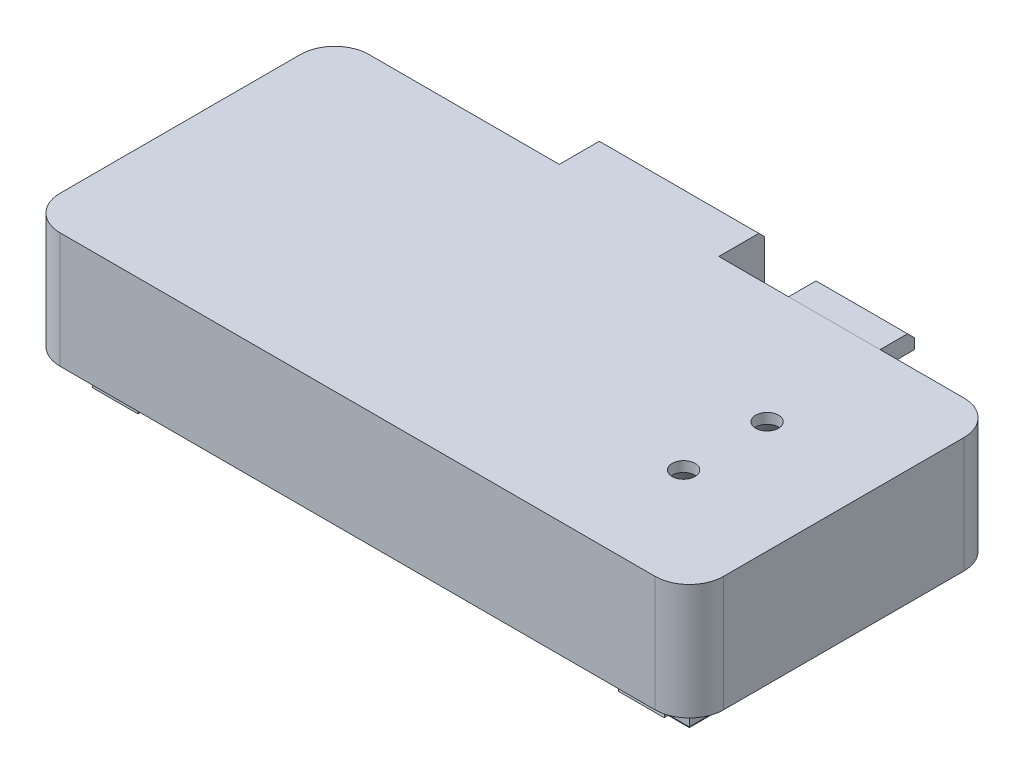
SolidWorks part; units mm, degrees
ref_plane "Front Plane" through (0, 0, 0) normal (0, 0, 1) x (1, 0, 0)
ref_plane "Top Plane" through (0, 0, 0) normal (0, 1, 0) x (1, 0, 0)
ref_plane "Right Plane" through (0, 0, 0) normal (1, 0, 0) x (0, 0, -1)
sketch "Sketch2" plane through (0, -591.8028, 0) normal (0, 1, 0) x (1, 0, 0)
  line L1 (-23.1805, -11.0534) -> (-23.1805, -19.9534)
  line L2 (-21.1805, -19.9534) -> (-21.1805, -11.0534)
  line L13 (34.8195, -25.4534) -> (34.8195, -4.4534)
  line L14 (31.8195, -1.4534) -> (-20.1805, -1.4534)
  line L15 (-23.1805, -4.4534) -> (-23.1805, -11.0534)
  line L16 (-23.1805, -11.0534) -> (-21.1805, -11.0534)
  line L17 (-21.1805, -11.0534) -> (-21.1805, -3.4534)
  line L18 (-21.1805, -3.4534) -> (-19.6805, -3.4534)
  line L19 (32.8195, -3.4534) -> (32.8195, -26.4534)
  line L20 (32.8195, -26.4534) -> (31.3195, -26.4534)
  line L21 (-21.1805, -26.4534) -> (-21.1805, -19.9534)
  line L22 (-21.1805, -19.9534) -> (-23.1805, -19.9534)
  line L23 (-23.1805, -19.9534) -> (-23.1805, -25.4534)
  line L24 (-20.1805, -28.4534) -> (31.8195, -28.4534)
  line L25 (34.8195, -25.4534) -> (34.8195, -4.4534)
  line L26 (31.8195, -1.4534) -> (-20.1805, -1.4534)
  line L27 (-23.1805, -4.4534) -> (-23.1805, -11.0534)
  line L28 (-23.1805, -11.0534) -> (-21.1805, -11.0534)
  line L29 (-21.1805, -11.0534) -> (-21.1805, -3.4534)
  line L30 (-21.1805, -3.4534) -> (-19.6805, -3.4534)
  line L31 (32.8195, -3.4534) -> (32.8195, -26.4534)
  line L32 (32.8195, -26.4534) -> (31.3195, -26.4534)
  line L33 (-21.1805, -26.4534) -> (-21.1805, -19.9534)
  line L34 (-21.1805, -19.9534) -> (-23.1805, -19.9534)
  line L35 (-23.1805, -19.9534) -> (-23.1805, -25.4534)
  line L36 (-20.1805, -28.4534) -> (31.8195, -28.4534)
  line L131 (26.3195, -3.4534) -> (31.3195, -3.4534)
  line L132 (26.3195, -3.4534) -> (31.3195, -3.4534)
  line L133 (31.3195, -3.4534) -> (32.8195, -3.4534)
  line L134 (31.3195, -3.4534) -> (32.8195, -3.4534)
  line L135 (31.3195, -26.4534) -> (26.3195, -26.4534)
  line L136 (31.3195, -26.4534) -> (26.3195, -26.4534)
  line L137 (-19.6805, -26.4534) -> (-21.1805, -26.4534)
  line L138 (-19.6805, -26.4534) -> (-21.1805, -26.4534)
  line L163 (-19.6805, -3.4534) -> (-14.6805, -3.4534)
  line L164 (-19.6805, -3.4534) -> (-14.6805, -3.4534)
  line L165 (-14.6805, -3.4534) -> (26.3195, -3.4534)
  line L166 (-14.6805, -3.4534) -> (26.3195, -3.4534)
  line L167 (26.3195, -26.4534) -> (-14.6805, -26.4534)
  line L168 (26.3195, -26.4534) -> (-14.6805, -26.4534)
  line L169 (-14.6805, -26.4534) -> (-19.6805, -26.4534)
  line L170 (-14.6805, -26.4534) -> (-19.6805, -26.4534)
  arc A4 (34.8195, -4.4534) -> (31.8195, -1.4534) centre (31.8195, -4.4534) ccw
  arc A5 (-20.1805, -1.4534) -> (-23.1805, -4.4534) centre (-20.1805, -4.4534) ccw
  arc A6 (-23.1805, -25.4534) -> (-20.1805, -28.4534) centre (-20.1805, -25.4534) ccw
  arc A7 (31.8195, -28.4534) -> (34.8195, -25.4534) centre (31.8195, -25.4534) ccw
  arc A8 (34.8195, -4.4534) -> (31.8195, -1.4534) centre (31.8195, -4.4534) ccw
  arc A9 (-20.1805, -1.4534) -> (-23.1805, -4.4534) centre (-20.1805, -4.4534) ccw
  arc A10 (-23.1805, -25.4534) -> (-20.1805, -28.4534) centre (-20.1805, -25.4534) ccw
  arc A11 (31.8195, -28.4534) -> (34.8195, -25.4534) centre (31.8195, -25.4534) ccw
  line M17 (34.8195, -25.4534) -> (34.8195, -4.4534)
  arc M18 (34.8195, -4.4534) -> (31.8195, -1.4534) centre (31.8195, -4.4534) ccw
  line M19 (31.8195, -1.4534) -> (-20.1805, -1.4534)
  arc M20 (-20.1805, -1.4534) -> (-23.1805, -4.4534) centre (-20.1805, -4.4534) ccw
  line M21 (-23.1805, -4.4534) -> (-23.1805, -11.0534)
  line M22 (-23.1805, -11.0534) -> (-21.1805, -11.0534)
  line M23 (-21.1805, -11.0534) -> (-21.1805, -3.4534)
  line M24 (-21.1805, -3.4534) -> (-19.6805, -3.4534)
  line M25 (32.8195, -3.4534) -> (32.8195, -26.4534)
  line M26 (32.8195, -26.4534) -> (31.3195, -26.4534)
  line M27 (-21.1805, -26.4534) -> (-21.1805, -19.9534)
  line M28 (-21.1805, -19.9534) -> (-23.1805, -19.9534)
  line M29 (-23.1805, -19.9534) -> (-23.1805, -25.4534)
  arc M30 (-23.1805, -25.4534) -> (-20.1805, -28.4534) centre (-20.1805, -25.4534) ccw
  line M31 (-20.1805, -28.4534) -> (31.8195, -28.4534)
  arc M32 (31.8195, -28.4534) -> (34.8195, -25.4534) centre (31.8195, -25.4534) ccw
  dimension "D1" = 0
extrude "Boss-Extrude1" add sketch "Sketch2" along normal blind 8.108 contours M32 M17 M18 M19 M20 M21 M22 M23 M24 M25 M26 M27 M28 M29 M30 M31 | L2 L1 M28 M22
sketch "Sketch3" plane through (0, -583.6948, 0) normal (0, 1, 0) x (1, 0, 0)
  line L4 (34.8195, -25.4534) -> (34.8195, -4.4534)
  line L5 (31.8195, -1.4534) -> (-20.1805, -1.4534)
  line L6 (-23.1805, -4.4534) -> (-23.1805, -25.4534)
  line L7 (-20.1805, -28.4534) -> (31.8195, -28.4534)
  line L8 (34.8195, -25.4534) -> (34.8195, -4.4534)
  line L9 (31.8195, -1.4534) -> (-20.1805, -1.4534)
  line L10 (-23.1805, -4.4534) -> (-23.1805, -25.4534)
  line L11 (-20.1805, -28.4534) -> (31.8195, -28.4534)
  arc A4 (31.8195, -28.4534) -> (34.8195, -25.4534) centre (31.8195, -25.4534) ccw
  arc A5 (34.8195, -4.4534) -> (31.8195, -1.4534) centre (31.8195, -4.4534) ccw
  arc A6 (-20.1805, -1.4534) -> (-23.1805, -4.4534) centre (-20.1805, -4.4534) ccw
  arc A7 (-23.1805, -25.4534) -> (-20.1805, -28.4534) centre (-20.1805, -25.4534) ccw
  arc A8 (31.8195, -28.4534) -> (34.8195, -25.4534) centre (31.8195, -25.4534) ccw
  arc A9 (34.8195, -4.4534) -> (31.8195, -1.4534) centre (31.8195, -4.4534) ccw
  arc A10 (-20.1805, -1.4534) -> (-23.1805, -4.4534) centre (-20.1805, -4.4534) ccw
  arc A11 (-23.1805, -25.4534) -> (-20.1805, -28.4534) centre (-20.1805, -25.4534) ccw
  dimension "D1" = 0
extrude "Boss-Extrude2" add sketch "Sketch3" along normal blind 2
sketch "Sketch4" plane through (0, -583.6948, 0) normal (0, -1, 0) x (1, 0, 0)
  line L0 (26.8195, 26.4534) -> (32.8195, 26.4534)
  line L1 (32.8195, 26.4534) -> (-21.1805, 26.4534) construction
  line L2 (32.8195, 26.4534) -> (32.8195, 24.4534)
  line L3 (32.8195, 3.4534) -> (32.8195, 26.4534) construction
  line L4 (32.8195, 24.4534) -> (26.8195, 24.4534)
  line L5 (26.8195, 24.4534) -> (26.8195, 26.4534)
  line L6 (32.8195, 5.4534) -> (26.8195, 5.4534)
  line L7 (26.8195, 5.4534) -> (26.8195, 3.4534)
  line L8 (-21.1805, 3.4534) -> (32.8195, 3.4534) construction
  line L9 (26.8195, 3.4534) -> (32.8195, 3.4534)
  line L10 (32.8195, 3.4534) -> (32.8195, 5.4534)
  line L11 (-21.1805, 26.4534) -> (-15.1805, 26.4534)
  line L12 (-15.1805, 26.4534) -> (-15.1805, 24.4534)
  line L13 (-15.1805, 24.4534) -> (-21.1805, 24.4534)
  line L14 (-21.1805, 26.4534) -> (-21.1805, 3.4534) construction
  line L15 (-21.1805, 24.4534) -> (-21.1805, 26.4534)
  line L16 (-21.1805, 5.4534) -> (-15.1805, 5.4534)
  line L17 (-15.1805, 5.4534) -> (-15.1805, 3.4534)
  line L18 (-15.1805, 3.4534) -> (-21.1805, 3.4534)
  line L19 (-21.1805, 3.4534) -> (-21.1805, 5.4534)
  line L21 (-0.6397, 26.4534) -> (6.2386, 26.4534)
  line L22 (-0.6397, 26.4534) -> (-0.6397, 24.4534)
  line L23 (-0.6397, 24.4534) -> (6.2386, 24.4534)
  line L24 (6.2386, 26.4534) -> (6.2386, 24.4534)
  dimension "D1" = 6
  dimension "D2" = 2
extrude "Boss-Extrude3" add sketch "Sketch4" along normal offset from surface (10.108 mm away) 2 up to face at (5.8195, -591.8028, 14.9534) offset beyond the face yes
sketch "Sketch5" plane through (0, -581.6948, 0) normal (0, 1, 0) x (1, 0, 0)
  line L0 (32.8195, -5.4534) -> (32.8195, -24.4534) construction
  line L1 (26.8195, -26.4534) -> (6.2386, -26.4534) construction
  circle A0 centre (25.0195, -11.8534) radius 1
  circle A1 centre (25.0195, -19.1534) radius 1
  dimension "D1" = 7.3
  dimension "D2" = 2
  dimension "D3" = 7.8
  dimension "D4" = 7.3
extrude "Cut-Extrude1" cut sketch "Sketch5" against normal up to next
chamfer "Chamfer1" distance 0.8 angle 54 2 edges at (25.0195, -583.6948, 12.8534) (25.0195, -583.6948, 20.1534)
sketch "Sketch6" plane through (26.8195, 0, 0) normal (-1, 0, 0) x (0, 0, 1)
  line L0 (3.4534, -592.8028) -> (3.2534, -593.8028)
  line L1 (3.4534, -593.8028) -> (3.4534, -591.8028) construction
  line L2 (3.2534, -593.8028) -> (3.4534, -593.8028)
  line L3 (3.4534, -593.8028) -> (3.4534, -592.8028)
  line L4 (3.4534, -593.8028) -> (5.4534, -593.8028) construction
  line L5 (26.4534, -593.8028) -> (26.6534, -593.8028)
  line L6 (26.6534, -593.8028) -> (26.4534, -592.8028)
  line L7 (26.4534, -591.8028) -> (26.4534, -583.6948) construction
  line L8 (26.4534, -592.8028) -> (26.4534, -593.8028)
  point P11 (0, 0)
  dimension "D1" = 0.2
  dimension "D2" = 1
extrude "Boss-Extrude4" add sketch "Sketch6" against normal offset from surface (4 mm away) 2 up to face at (32.8195, -592.8028, 4.4534)
sketch "Sketch7" plane through (-15.1805, 0, 0) normal (1, 0, 0) x (0, 0, -1)
  line L5 (-26.4534, -593.8028) -> (-26.6534, -593.8028)
  line L6 (-26.6534, -593.8028) -> (-26.4534, -591.8028)
  line L7 (-26.4534, -591.8028) -> (-26.4534, -593.8028)
  line L8 (-3.4534, -593.8028) -> (-3.2534, -593.8028)
  line L9 (-3.2534, -593.8028) -> (-3.4534, -591.8028)
  line L10 (-3.4534, -593.8028) -> (-3.4534, -591.8028) construction
  line L11 (-3.4534, -591.8028) -> (-3.4534, -593.8028)
  line L12 (-5.4534, -593.8028) -> (-3.4534, -593.8028) construction
  point P2 (-2.3575, -2.8108)
  point P7 (-2.9015, -0.8108)
  point P10 (-2.7015, -2.8108)
  dimension "D3" = 2
  dimension "D4" = 0.2
extrude "Boss-Extrude5" add sketch "Sketch7" against normal offset from surface (4 mm away) 2 up to face at (-21.1805, -592.8028, 25.4534)
chamfer "Chamfer2" distance 0.15 angle 54 15 edges at (28.8195, -593.8028, 3.2534) (-17.1805, -593.8028, 3.2534) (-21.1805, -593.8028, 25.4534) (-20.1805, -593.8028, 26.4534) (2.7994, -593.8028, 26.4534) (31.8195, -593.8028, 26.4534) (32.8195, -593.8028, 25.4534) (26.8195, -593.8028, 4.3534) (29.8195, -593.8028, 5.4534) (32.8195, -593.8028, 4.4534) (31.8195, -593.8028, 3.4534) (-15.1805, -593.8028, 4.3534) (-20.1805, -593.8028, 3.4534) (-21.1805, -593.8028, 4.4534) (-18.1805, -593.8028, 5.4534)
sketch "Sketch9" plane through (0, 0, 3.4534) normal (0, 0, 1) x (1, 0, 0)
  line L0 (17.9568, -584.9948) -> (23.0368, -584.9948) construction
  line L1 (-15.1805, -583.6948) -> (26.8195, -583.6948) construction
  circle A0 centre (17.9568, -584.9948) radius 0.75
  circle A1 centre (20.4968, -584.9948) radius 0.75
  circle A2 centre (23.0368, -584.9948) radius 0.75
  dimension "D1" = 5.08
  dimension "D2" = 1.5
  dimension "D3" = 1.3
extrude "Cut-Extrude3" cut sketch "Sketch9" against normal up to next
sketch "Sketch10" plane through (0, 0, 1.4534) normal (0, 0, -1) x (-1, 0, 0)
  line L0 (-16.9968, -584.9948) -> (-23.9968, -584.9948) construction
  line L1 (-16.9968, -586.7448) -> (-23.9968, -586.7448)
  line L2 (-16.9968, -583.2448) -> (-23.9968, -583.2448)
  arc A0 (-16.9968, -586.7448) -> (-16.9968, -583.2448) centre (-16.9968, -584.9948) ccw
  arc A1 (-23.9968, -583.2448) -> (-23.9968, -586.7448) centre (-23.9968, -584.9948) ccw
  circle A2 centre (-20.4968, -584.9948) radius 0.75 construction
  point P2 (-20.4968, -584.9948)
  point P7 (0, 0)
  dimension "D1" = 3.5
  dimension "D2" = 7
extrude "Cut-Extrude4" cut sketch "Sketch10" against normal blind 1.2 draft 45
sketch "Sketch11" plane through (0, -583.6948, 0) normal (0, -1, 0) x (1, 0, 0)
  line L0 (20.4968, 3.4534) -> (20.4968, 6.9934) construction
  line L1 (-15.1805, 3.4534) -> (26.8195, 3.4534) construction
  line L2 (21.2468, 3.4534) -> (19.7468, 3.4534) construction
  line L3 (23.8031, 6.9934) -> (23.8031, 8.9934)
  line L4 (16.4968, 6.9934) -> (24.4968, 6.9934)
  line L5 (16.4968, 6.9934) -> (16.4968, 8.9934)
  line L6 (16.4968, 8.9934) -> (24.4968, 8.9934)
  line L7 (24.4968, 6.9934) -> (24.4968, 8.9934)
  line L8 (24.4968, 3.4534) -> (16.4968, 3.4534)
  line L9 (24.4968, 3.4534) -> (24.4968, 4.4534)
  line L10 (24.4968, 4.4534) -> (16.4968, 4.4534)
  line L11 (16.4968, 3.4534) -> (16.4968, 4.4534)
  line L12 (23.8031, 3.4534) -> (22.6031, 3.4534)
  line L13 (23.8031, 3.4534) -> (23.8031, 4.4534)
  line L14 (23.8031, 4.4534) -> (22.6031, 4.4534)
  line L15 (22.6031, 3.4534) -> (22.6031, 4.4534)
  line L16 (21.0968, 3.4534) -> (19.8968, 3.4534)
  line L17 (21.0968, 3.4534) -> (21.0968, 4.4534)
  line L18 (21.0968, 4.4534) -> (19.8968, 4.4534)
  line L19 (19.8968, 3.4534) -> (19.8968, 4.4534)
  line L20 (18.7335, 3.4534) -> (17.5335, 3.4534)
  line L21 (18.7335, 3.4534) -> (18.7335, 4.4534)
  line L22 (18.7335, 4.4534) -> (17.5335, 4.4534)
  line L23 (17.5335, 3.4534) -> (17.5335, 4.4534)
  line L24 (22.6031, 6.9934) -> (22.6031, 8.9934)
  line L25 (19.8968, 6.9934) -> (19.8968, 8.9934)
  line L26 (21.0968, 6.9934) -> (21.0968, 8.9934)
  line L27 (18.7335, 6.9934) -> (18.7335, 8.9934)
  line L28 (17.5335, 6.9934) -> (17.5335, 8.9934)
  point P26 (20.4968, 3.4534)
  line M9 (-15.1805, 3.4534) -> (26.8195, 3.4534)
  dimension "D1" = 1
  dimension "D2" = 2
  dimension "D3" = 8
  dimension "D4" = 2.54
  dimension "D5" = 0.6
extrude "Boss-Extrude6" add sketch "Sketch11" along normal blind 2.5 contours L13 L9 L10 M9 | L17 L15 L10 M9 | L21 L19 L10 M9 | L23 L10 L11 M9 | L4 L7 L6 L3 | L26 L4 L24 L6 | L27 L4 L25 L6 | L4 L28 L6 L5
sketch "Sketch12" plane through (0, 0, 1.4534) normal (0, 0, -1) x (-1, 0, 0)
  line L0 (-31.8195, -581.6948) -> (20.1805, -581.6948) construction
  line L1 (-24.4968, -581.6948) -> (-16.4968, -581.6948)
  line L2 (-24.4968, -581.6948) -> (-24.4968, -583.1948)
  line L3 (-24.4968, -583.1948) -> (-16.4968, -583.1948)
  line L4 (-16.4968, -581.6948) -> (-16.4968, -583.1948)
  line L5 (-20.4968, -584.9948) -> (-20.4968, -583.1948) construction
  point P6 (-20.4968, -583.1948)
  point P10 (-20.4968, -245.8559)
  point P11 (-20.4968, -245.8559)
  dimension "D1" = 1.5
  dimension "D2" = 8
extrude "Boss-Extrude7" add sketch "Sketch12" along normal blind 3 separate body
chamfer "Chamfer4" distance 0.6 angle 45 3 edges at (16.4968, -581.6948, -0.0466) (24.4968, -581.6948, -0.0466) (20.4968, -581.6948, -1.5466)
sketch "Sketch14" plane through (0, -583.6948, 0) normal (0, -1, 0) x (1, 0, 0)
  line L0 (7.9245, 3.4534) -> (7.9245, 8.9431)
  line L1 (-15.1805, 3.4534) -> (16.4968, 3.4534) construction
  line L2 (7.9245, 8.9431) -> (-1.0755, 8.9431)
  line L3 (-1.0755, 8.9431) -> (-1.0755, 3.4534)
  line L4 (-1.0755, 3.4534) -> (7.9245, 3.4534)
  line L5 (6.6245, 3.4534) -> (6.6245, 8.9431)
  line L6 (5.2245, 3.4534) -> (5.2245, 8.9431)
  line L7 (1.6245, 3.4534) -> (1.6245, 8.9431)
  line L8 (0.2245, 3.4534) -> (0.2245, 8.9431)
  line L9 (3.9245, 3.4534) -> (3.9245, 8.9431)
  line L10 (2.9245, 3.4534) -> (2.9245, 8.9431)
  line L11 (7.9245, 4.4534) -> (-1.0755, 4.4534)
  line L12 (17.5335, 4.4534) -> (16.4968, 4.4534) construction
  line L13 (7.9245, 6.9934) -> (-1.0755, 6.9934)
  line L14 (16.4968, 6.9934) -> (17.5335, 6.9934) construction
  line L15 (3.9245, 6.1982) -> (2.9245, 6.1982) construction
  line L16 (3.4245, 6.1982) -> (3.4245, 4.4534) construction
  point P28 (3.4245, 4.4534)
  line M40 (-15.1805, 3.4534) -> (16.4968, 3.4534)
  dimension "D1" = 1.3
  dimension "D2" = 1.3
  dimension "D3" = 1.3
  dimension "D4" = 1.3
  dimension "D5" = 1
  dimension "D6" = 9
extrude "Boss-Extrude8" add sketch "Sketch14" along normal blind 4 contours L0 L11 L5 L4 | L6 L11 L9 M40 | L10 L11 L7 L4 | L8 L11 L3 M40 | L13 L8 L2 L3 | L13 L10 L2 L7 | L13 L6 L2 L9 | L13 L0 L2 L5
sketch "Sketch15" plane through (0, 0, 3.4534) normal (0, 0, 1) x (1, 0, 0)
  line L0 (5.9645, -584.9948) -> (0.8845, -584.9948) construction
  line L1 (3.9245, -583.6948) -> (2.9245, -583.6948) construction
  line L2 (3.4245, -583.6948) -> (3.4245, -584.9948) construction
  line L3 (7.9245, -583.6948) -> (16.4968, -583.6948) construction
  circle A0 centre (5.9645, -584.9948) radius 0.75
  circle A1 centre (3.4245, -584.9948) radius 0.75
  circle A2 centre (0.8845, -584.9948) radius 0.75
  circle A3 centre (3.4245, -587.5348) radius 0.75
  circle A4 centre (0.8845, -587.5348) radius 0.75
  circle A5 centre (5.9645, -587.5348) radius 0.75
  point P2 (3.1476, -429.854)
  point P18 (3.1476, -429.2166)
  point P19 (3.2082, -429.2166)
  dimension "D3" = 1.5
  dimension "D1" = 5.08
  dimension "D4" = 1.3
  dimension "D2" = 2
extrude "Cut-Extrude5" cut sketch "Sketch15" against normal up to next (2 mm away)
sketch "Sketch16" plane through (0, 0, 1.4534) normal (0, 0, -1) x (-1, 0, 0)
  line L0 (-3.4245, -584.9948) -> (-3.4245, -587.5348) construction
  line L1 (-8.8962, -582.5108) -> (2.0471, -582.5108)
  line L2 (-8.8962, -582.5108) -> (-8.8962, -590.0188)
  line L3 (-8.8962, -590.0188) -> (2.0471, -590.0188)
  line L4 (2.0471, -582.5108) -> (2.0471, -590.0188)
  line L5 (-3.4245, -586.2648) -> (2.0471, -586.2648) construction
  line L6 (-3.4245, -584.9948) -> (-3.4245, -582.5108) construction
  point P10 (0, 0)
extrude "Cut-Extrude6" cut sketch "Sketch16" against normal blind 1 draft 45
sketch "Sketch17" plane through (0, 0, 1.4534) normal (0, 0, -1) x (-1, 0, 0)
  line L0 (-31.8195, -581.6948) -> (20.1805, -581.6948) construction
  line L1 (-8.8962, -582.5108) -> (2.0471, -582.5108)
  line L2 (-8.8962, -582.5108) -> (-8.8962, -581.6948)
  line L3 (-8.8962, -581.6948) -> (2.0471, -581.6948)
  line L4 (2.0471, -582.5108) -> (2.0471, -581.6948)
  line L5 (-8.8962, -590.0188) -> (2.0471, -590.0188) construction
  line L6 (-8.8962, -581.6948) -> (-10.3962, -581.6948)
  line L7 (-8.8962, -581.6948) -> (-8.8962, -590.0188)
  line L8 (-8.8962, -590.0188) -> (-10.3962, -590.0188)
  line L9 (-10.3962, -581.6948) -> (-10.3962, -590.0188)
  line L10 (2.0471, -581.6948) -> (3.5471, -581.6948)
  line L11 (2.0471, -581.6948) -> (2.0471, -590.0188)
  line L12 (2.0471, -590.0188) -> (3.5471, -590.0188)
  line L13 (3.5471, -581.6948) -> (3.5471, -590.0188)
  line L14 (2.0471, -590.0188) -> (2.0471, -582.5108) construction
  line M14 (-8.8962, -590.0188) -> (-8.8962, -582.5108)
  line M15 (-8.8962, -582.5108) -> (2.0471, -582.5108)
  line M16 (2.0471, -582.5108) -> (2.0471, -590.0188)
  line M23 (20.1805, -581.6948) -> (-31.8195, -581.6948)
  dimension "D1" = 1.5
extrude "Boss-Extrude9" add sketch "Sketch17" along normal blind 4 contours L4 L2 M15 M23 | L9 L8 L2 M23 M14 | L13 L4 L12 M23 M16
chamfer "Chamfer5" distance 0.5 angle 45 1 edges at (3.4245, -581.6948, -2.5466)
equation "\"riserpin\"=1.3"
equation "\"D1@Sketch14\"=\"riserpin\""
equation "\"D2@Sketch14\"=\"riserpin\""
equation "\"D3@Sketch14\"=\"riserpin\""
equation "\"D4@Sketch14\"=\"riserpin\""
